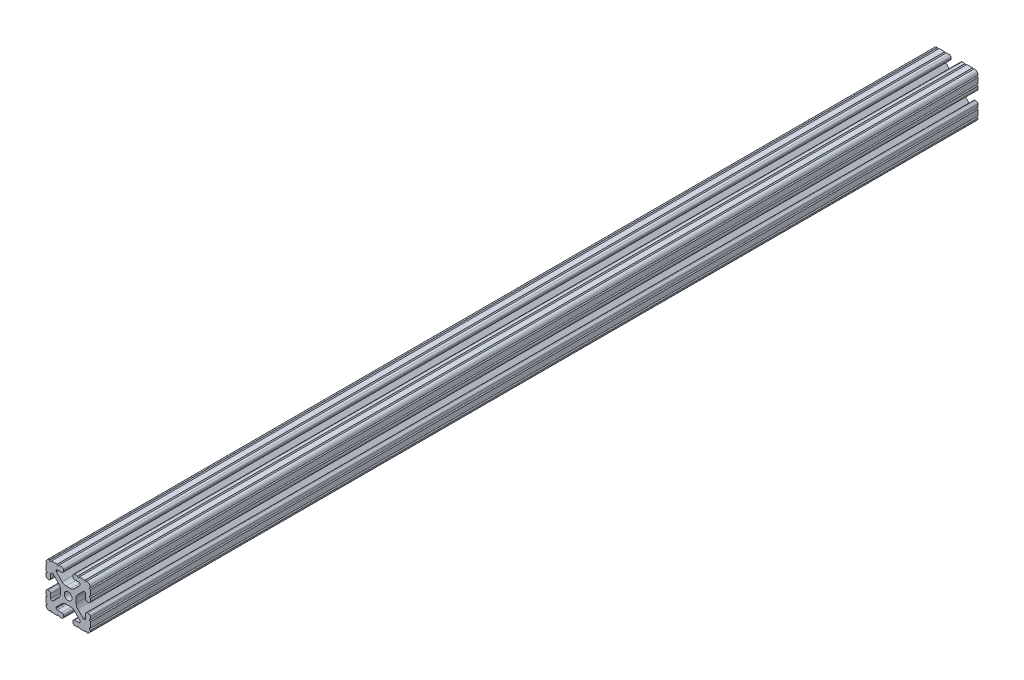
SolidWorks part; units mm, degrees
ref_plane "Front Plane" through (0, 0, 0) normal (0, 0, 1) x (1, 0, 0)
ref_plane "Top Plane" through (0, 0, 0) normal (0, 1, 0) x (1, 0, 0)
ref_plane "Right Plane" through (0, 0, 0) normal (1, 0, 0) x (0, 0, -1)
sketch "Sketch1" plane through (0, 0, 0) normal (1, 0, 0) x (0, 0, -1)
  line L0 (0, 0) -> (762, 0)
  dimension "D1" = 762
other "15 1515 PROFILE(1)"
ref_plane "Plane1" through (0, 0, 0) normal (0, 0, -1) x (0, 1, 0)
sketch "Sketch11" plane through (0, 0, 0) normal (0, 0, -1) x (0, 1, 0)
  line L0 (0, 25.6181) -> (0, -24.623) construction
  line L1 (-20.8943, 0) -> (20.4607, 0) construction
  line L2 (-10.0229, 12.9148) -> (-5.2522, 8.144)
  line L3 (-10.287, 14.0843) -> (-10.287, 13.5524)
  line L4 (-5.6176, 14.986) -> (-9.3853, 14.986)
  line L5 (-4.064, 17.4964) -> (-4.064, 16.5396)
  line L6 (-7.9742, 19.05) -> (-5.6176, 19.05)
  line L7 (-14.3277, 19.05) -> (-9.4982, 19.05)
  line L8 (-19.05, 9.4961) -> (-19.05, 14.3277)
  line L9 (-19.05, 5.6176) -> (-19.05, 7.9763)
  line L10 (-16.5396, 4.064) -> (-17.4964, 4.064)
  line L11 (-14.986, 9.3853) -> (-14.986, 5.6176)
  line L12 (-13.516, 10.287) -> (-14.0843, 10.287)
  line L13 (-8.1476, 5.2921) -> (-12.8784, 10.0229)
  line L14 (-6.7564, -1.9335) -> (-6.7564, 1.9335)
  line L15 (-12.8784, -10.0229) -> (-8.1476, -5.2921)
  line L16 (-14.0843, -10.287) -> (-13.516, -10.287)
  line L17 (-14.986, -5.6176) -> (-14.986, -9.3853)
  line L18 (-17.4964, -4.064) -> (-16.5396, -4.064)
  line L19 (-19.05, -7.9763) -> (-19.05, -5.6176)
  line L20 (-19.05, -14.3277) -> (-19.05, -9.4961)
  line L21 (-9.4961, -19.05) -> (-14.3277, -19.05)
  line L22 (-5.6176, -19.05) -> (-7.9763, -19.05)
  line L23 (-4.064, -17.4964) -> (-4.064, -16.5396)
  line L24 (10.0229, -12.9148) -> (5.2522, -8.144)
  line L25 (10.287, -14.0843) -> (10.287, -13.5524)
  line L26 (5.6176, -14.986) -> (9.3853, -14.986)
  line L27 (-5.6176, 19.05) -> (5.6176, 19.05) construction
  line L28 (-1.9022, 6.7564) -> (1.9022, 6.7564)
  line L29 (-1.9022, -6.7564) -> (1.9022, -6.7564)
  line L30 (19.05, 5.6176) -> (19.05, -5.6176) construction
  line L31 (-5.6176, -14.986) -> (-9.3853, -14.986)
  line L32 (-10.287, -14.0843) -> (-10.287, -13.5524)
  line L33 (-10.0229, -12.9148) -> (-5.2522, -8.144)
  line L34 (5.6176, -19.05) -> (-5.6176, -19.05) construction
  line L35 (-19.05, -5.6176) -> (-19.05, 5.6176) construction
  line L37 (-19.05, 19.05) -> (19.05, 19.05) construction
  line L38 (-19.05, 19.05) -> (-19.05, -19.05) construction
  line L39 (-19.05, -19.05) -> (19.05, -19.05) construction
  line L40 (19.05, 19.05) -> (19.05, -19.05) construction
  line L66 (4.064, -16.5396) -> (4.064, -17.4964)
  line L67 (5.6176, -19.05) -> (7.9763, -19.05)
  line L68 (9.4961, -19.05) -> (14.3277, -19.05)
  line L69 (19.05, -14.3277) -> (19.05, -9.4961)
  line L70 (19.05, -7.9763) -> (19.05, -5.6176)
  line L71 (17.4964, -4.064) -> (16.5396, -4.064)
  line L72 (14.986, -5.6176) -> (14.986, -9.3853)
  line L73 (14.0843, -10.287) -> (13.516, -10.287)
  line L74 (12.8784, -10.0229) -> (8.1476, -5.2921)
  line L75 (6.7564, -1.9335) -> (6.7564, 1.9335)
  line L76 (8.1476, 5.2921) -> (12.8784, 10.0229)
  line L77 (13.516, 10.287) -> (14.0843, 10.287)
  line L78 (14.986, 9.3853) -> (14.986, 5.6176)
  line L79 (16.5396, 4.064) -> (17.4964, 4.064)
  line L80 (19.05, 5.6176) -> (19.05, 7.9763)
  line L81 (19.05, 9.4961) -> (19.05, 14.3277)
  line L82 (14.3277, 19.05) -> (9.4982, 19.05)
  line L83 (7.9742, 19.05) -> (5.6176, 19.05)
  line L84 (4.064, 17.4964) -> (4.064, 16.5396)
  line L85 (5.6176, 14.986) -> (9.3853, 14.986)
  line L86 (10.287, 14.0843) -> (10.287, 13.5524)
  line L87 (10.0229, 12.9148) -> (5.2522, 8.144)
  arc A0 (-10.0229, 12.9148) -> (-10.287, 13.5524) centre (-9.3853, 13.5524) cw
  circle A1 centre (0, 0) radius 3.3274
  arc A2 (-10.287, 14.0843) -> (-9.3853, 14.986) centre (-9.3853, 14.0843) cw
  arc A3 (-4.064, 16.5396) -> (-5.6176, 14.986) centre (-5.6176, 16.5396) cw
  arc A4 (-5.6176, 19.05) -> (-4.064, 17.4964) centre (-5.6176, 17.4964) cw
  arc A5 (-7.9742, 19.05) -> (-9.4982, 19.05) centre (-8.7362, 19.05) cw
  arc A6 (-14.3277, 19.05) -> (-15.8475, 19.05) centre (-15.0876, 18.9933) cw
  arc A7 (-19.05, 15.8475) -> (-15.8475, 19.05) centre (-15.8751, 15.8751) cw
  arc A8 (-19.05, 15.8475) -> (-19.05, 14.3277) centre (-18.9933, 15.0876) cw
  arc A9 (-19.05, 9.4961) -> (-19.05, 7.9763) centre (-18.9933, 8.7362) cw
  arc A10 (-17.4964, 4.064) -> (-19.05, 5.6176) centre (-17.4964, 5.6176) cw
  arc A11 (-14.986, 5.6176) -> (-16.5396, 4.064) centre (-16.5396, 5.6176) cw
  arc A12 (-14.986, 9.3853) -> (-14.0843, 10.287) centre (-14.0843, 9.3853) cw
  arc A13 (-13.516, 10.287) -> (-12.8784, 10.0229) centre (-13.516, 9.3853) cw
  arc A14 (-8.1476, 5.2921) -> (-6.7564, 1.9335) centre (-11.5062, 1.9335) cw
  arc A15 (-6.7564, -1.9335) -> (-8.1476, -5.2921) centre (-11.5062, -1.9335) cw
  arc A16 (-12.8784, -10.0229) -> (-13.516, -10.287) centre (-13.516, -9.3853) cw
  arc A17 (-14.0843, -10.287) -> (-14.986, -9.3853) centre (-14.0843, -9.3853) cw
  arc A18 (-16.5396, -4.064) -> (-14.986, -5.6176) centre (-16.5396, -5.6176) cw
  arc A19 (-19.05, -5.6176) -> (-17.4964, -4.064) centre (-17.4964, -5.6176) cw
  arc A20 (-19.05, -7.9763) -> (-19.05, -9.4961) centre (-18.9933, -8.7362) cw
  arc A21 (-19.05, -14.3277) -> (-19.05, -15.8475) centre (-18.9933, -15.0876) cw
  arc A22 (-15.8475, -19.05) -> (-19.05, -15.8475) centre (-15.8751, -15.8751) cw
  arc A23 (-15.8475, -19.05) -> (-14.3277, -19.05) centre (-15.0876, -18.9933) cw
  arc A24 (-9.4961, -19.05) -> (-7.9763, -19.05) centre (-8.7362, -18.9933) cw
  arc A25 (-4.064, -17.4964) -> (-5.6176, -19.05) centre (-5.6176, -17.4964) cw
  arc A26 (-5.2522, -8.144) -> (-1.9022, -6.7564) centre (-1.9022, -11.494) cw
  arc A27 (1.9022, -6.7564) -> (5.2522, -8.144) centre (1.9022, -11.494) cw
  arc A28 (10.0229, -12.9148) -> (10.287, -13.5524) centre (9.3853, -13.5524) cw
  arc A29 (10.287, -14.0843) -> (9.3853, -14.986) centre (9.3853, -14.0843) cw
  arc A30 (4.064, -16.5396) -> (5.6176, -14.986) centre (5.6176, -16.5396) cw
  arc A31 (-4.064, -16.5396) -> (-5.6176, -14.986) centre (-5.6176, -16.5396) ccw
  arc A32 (-10.287, -14.0843) -> (-9.3853, -14.986) centre (-9.3853, -14.0843) ccw
  arc A33 (-10.0229, -12.9148) -> (-10.287, -13.5524) centre (-9.3853, -13.5524) ccw
  arc A79 (4.064, -17.4964) -> (5.6176, -19.05) centre (5.6176, -17.4964) ccw
  arc A80 (9.4961, -19.05) -> (7.9763, -19.05) centre (8.7362, -18.9933) ccw
  arc A81 (15.8475, -19.05) -> (14.3277, -19.05) centre (15.0876, -18.9933) ccw
  arc A82 (15.8475, -19.05) -> (19.05, -15.8475) centre (15.8751, -15.8751) ccw
  arc A83 (19.05, -14.3277) -> (19.05, -15.8475) centre (18.9933, -15.0876) ccw
  arc A84 (19.05, -7.9763) -> (19.05, -9.4961) centre (18.9933, -8.7362) ccw
  arc A85 (19.05, -5.6176) -> (17.4964, -4.064) centre (17.4964, -5.6176) ccw
  arc A86 (16.5396, -4.064) -> (14.986, -5.6176) centre (16.5396, -5.6176) ccw
  arc A87 (14.0843, -10.287) -> (14.986, -9.3853) centre (14.0843, -9.3853) ccw
  arc A88 (12.8784, -10.0229) -> (13.516, -10.287) centre (13.516, -9.3853) ccw
  arc A89 (6.7564, -1.9335) -> (8.1476, -5.2921) centre (11.5062, -1.9335) ccw
  arc A90 (8.1476, 5.2921) -> (6.7564, 1.9335) centre (11.5062, 1.9335) ccw
  arc A91 (13.516, 10.287) -> (12.8784, 10.0229) centre (13.516, 9.3853) ccw
  arc A92 (14.986, 9.3853) -> (14.0843, 10.287) centre (14.0843, 9.3853) ccw
  arc A93 (14.986, 5.6176) -> (16.5396, 4.064) centre (16.5396, 5.6176) ccw
  arc A94 (17.4964, 4.064) -> (19.05, 5.6176) centre (17.4964, 5.6176) ccw
  arc A95 (19.05, 9.4961) -> (19.05, 7.9763) centre (18.9933, 8.7362) ccw
  arc A96 (19.05, 15.8475) -> (19.05, 14.3277) centre (18.9933, 15.0876) ccw
  arc A97 (19.05, 15.8475) -> (15.8475, 19.05) centre (15.8751, 15.8751) ccw
  arc A98 (14.3277, 19.05) -> (15.8475, 19.05) centre (15.0876, 18.9933) ccw
  arc A99 (7.9742, 19.05) -> (9.4982, 19.05) centre (8.7362, 19.05) ccw
  arc A100 (5.6176, 19.05) -> (4.064, 17.4964) centre (5.6176, 17.4964) ccw
  arc A101 (4.064, 16.5396) -> (5.6176, 14.986) centre (5.6176, 16.5396) ccw
  arc A102 (10.287, 14.0843) -> (9.3853, 14.986) centre (9.3853, 14.0843) ccw
  arc A103 (10.0229, 12.9148) -> (10.287, 13.5524) centre (9.3853, 13.5524) ccw
  arc A104 (1.9022, 6.7564) -> (5.2522, 8.144) centre (1.9022, 11.494) ccw
  arc A105 (-5.2522, 8.144) -> (-1.9022, 6.7564) centre (-1.9022, 11.494) ccw
  point P146 (-19.05, 0)
  point P152 (0, 19.05)
  point P153 (19.05, 0)
  point P154 (0, -19.05)
  point P159 (-19.05, 19.05)
  point P160 (19.05, 19.05)
  point P161 (19.05, -19.05)
  point P162 (-19.05, -19.05)
  point P163 (0, 0)
  point P164 (0, 0)
  dimension "D1" = 6.6548
  dimension "D2" = 19.05
  dimension "D3" = 38.1
  dimension "D4" = 20.574
  dimension "D5" = 13.5128
  dimension "D6" = 4.064
  dimension "D7" = 8.128
  dimension "D8" = 4.064
  dimension "D9" = 12.2936
